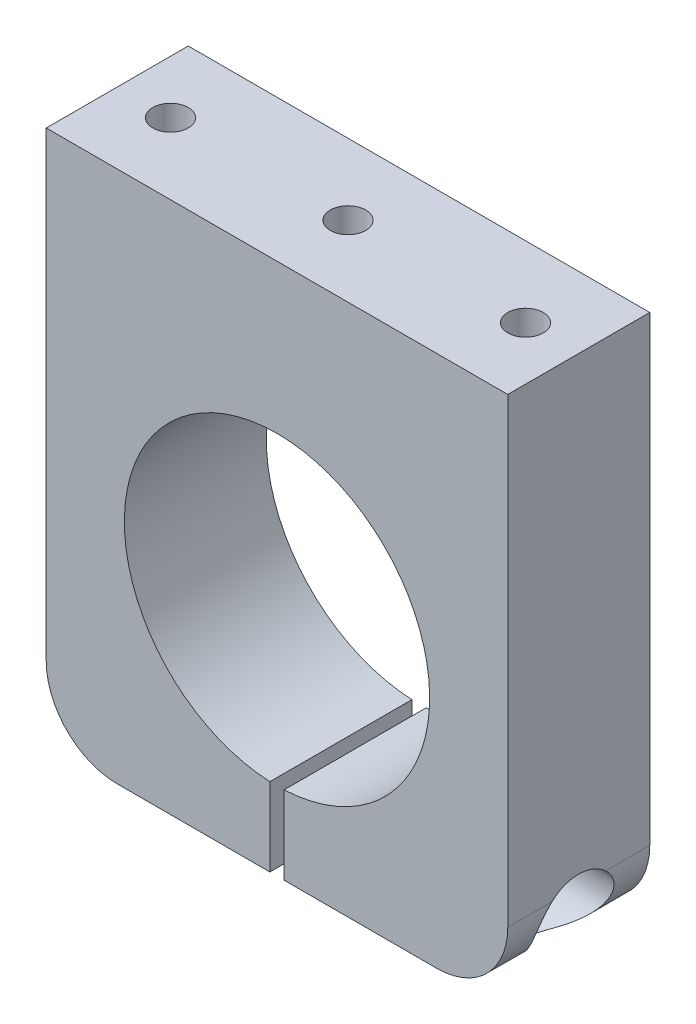
SolidWorks part; units mm, degrees
material "5454-H111"
ref_plane "Ebene vorne" through (0, 0, 0) normal (0, 0, 1) x (1, 0, 0)
ref_plane "Ebene oben" through (0, 0, 0) normal (0, 1, 0) x (1, 0, 0)
ref_plane "Ebene rechts" through (0, 0, 0) normal (1, 0, 0) x (0, 0, -1)
sketch "Skizze1" plane through (0, 0, 0) normal (0, 0, 1) x (1, 0, 0)
  line L0 (0, 53.478) -> (0, -69.2003) construction
  line L1 (-32.5, 42.5) -> (32.5, 42.5)
  line L2 (32.5, 42.5) -> (32.5, -22.5)
  line L3 (22.5, -32.5) -> (1, -32.5)
  line L4 (1, -21.4767) -> (1, -32.5)
  line L5 (-32.5, 42.5) -> (-32.5, -22.5)
  line L6 (-1, -21.4767) -> (-1, -32.5)
  line L7 (-22.5, -32.5) -> (-1, -32.5)
  arc A0 (1, -21.4767) -> (-1, -21.4767) centre (0, 0) ccw
  arc A1 (32.5, -22.5) -> (22.5, -32.5) centre (22.5, -22.5) cw
  arc A2 (-32.5, -22.5) -> (-22.5, -32.5) centre (-22.5, -22.5) ccw
  point P1 (0, 21.5)
  point P17 (0, 42.5)
  dimension "D1" = 43
  dimension "D2" = 10
  dimension "D3" = 65
  dimension "D4" = 75
  dimension "D5" = 42.5
  dimension "D6" = 2
  dimension "D7" = 21
extrude "Aufsatz-Linear austragen1" add sketch "Skizze1" along normal blind 20
hole_wizard "M6 Gewindebohrung1" positions "Skizze2" profile "Skizze3" tap size "M6" standard "DIN"
sketch "Skizze2" plane through (0, 42.5, 0) normal (0, 1, 0) x (1, 0, 0)
  line L0 (0, 0) -> (0, -27.3625) construction
  line L3 (-32.5, -10) -> (32.5, -10) construction
  line L4 (-32.5, -20) -> (-32.5, 0) construction
  line L5 (32.5, -20) -> (32.5, 0) construction
  point P17 (0, -10)
  point P19 (25, -10)
  point P23 (-25, -10)
  dimension "D1" = 25
sketch "Skizze3" plane through (-25, 42.5, 10) normal (1, 0, 0) x (0, 0, 1)
  line L0 (0, 0) -> (0, 18.5022)
  line L1 (0, 18.5022) -> (2.5, 17)
  line L2 (2.5, 17) -> (2.5, 0)
  line L5 (2.5, 0) -> (0, 0)
  line L10 (0, 18.5022) -> (-2.5, 17) construction
  line L11 (0, -6.35) -> (0, 107.95) construction
  dimension "Bohrerdurchmesser" = 5
  dimension "Bohrungstiefe" = 17
  dimension "Spitzenwinkel" = 118
cosmetic thread "Bohrungsgewinde1" parameters "D1"=12, "D2"=6
cosmetic thread "Bohrungsgewinde2" parameters "D1"=12, "D2"=6
cosmetic thread "Bohrungsgewinde3" parameters "D1"=12, "D2"=6
sketch "Skizze4" plane through (0, 0, 0) normal (1, 0, 0) x (0, 0, -1)
  line L0 (-10, 42.5) -> (-10, -34.0473) construction
  line L1 (-20, 42.5) -> (0, 42.5) construction
  line L2 (-20, -32.5) -> (0, -32.5) construction
  circle A0 centre (-10, -26.5) radius 3
  dimension "D1" = 6
  dimension "D2" = 6
extrude "Schnitt-Linear austragen1" cut sketch "Skizze4" along normal blind 40
sketch "Skizze5" plane through (0, 0, 0) normal (1, 0, 0) x (0, 0, -1)
  circle A0 centre (-10, -26.5) radius 5.5
  dimension "D1" = 11
extrude "Schnitt-Linear austragen2" cut sketch "Skizze5" along normal blind 20 from offset 20
